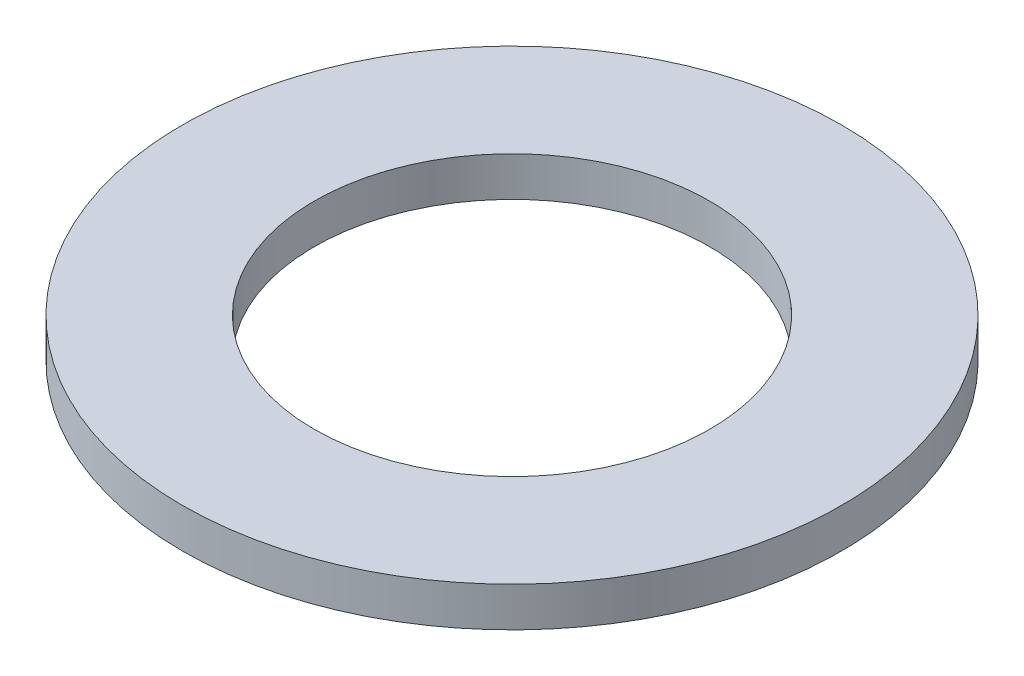
SolidWorks part; units mm, degrees
ref_plane "Front Plane" through (0, 0, 0) normal (0, 0, 1) x (1, 0, 0)
ref_plane "Top Plane" through (0, 0, 0) normal (0, 1, 0) x (1, 0, 0)
ref_plane "Right Plane" through (0, 0, 0) normal (1, 0, 0) x (0, 0, -1)
sketch "Sketch1" plane through (0, 0, 0) normal (0, 1, 0) x (1, 0, 0)
  circle A0 centre (0, 0) radius 2.5
  circle A1 centre (0, 0) radius 1.5
  dimension "D1" = 5
  dimension "D2" = 3
extrude "Boss-Extrude1" add sketch "Sketch1" along normal blind 0.3
